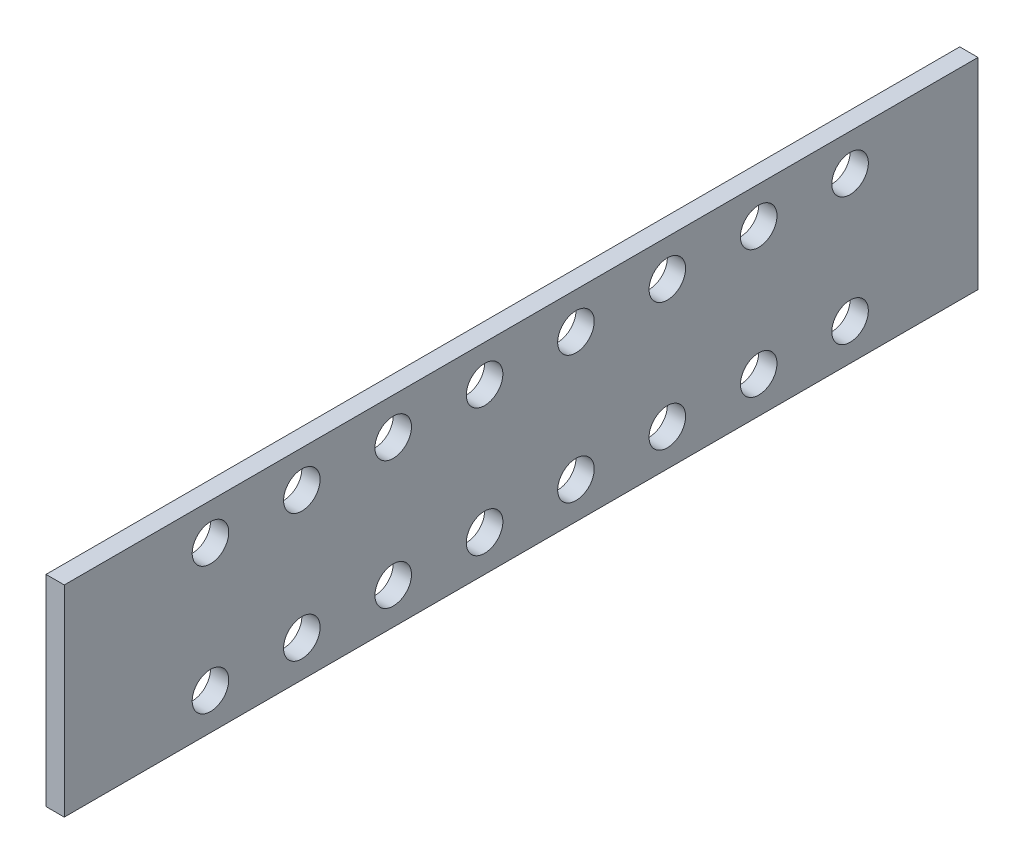
SolidWorks part; units mm, degrees
ref_plane "Front Plane" through (0, 0, 0) normal (0, 0, 1) x (1, 0, 0)
ref_plane "Top Plane" through (0, 0, 0) normal (0, 1, 0) x (1, 0, 0)
ref_plane "Right Plane" through (0, 0, 0) normal (1, 0, 0) x (0, 0, -1)
sketch "Sketch2" plane through (0, 0, 0) normal (1, 0, 0) x (0, 0, -1)
  line L1 (0, 0) -> (500, 0)
  line L2 (0, 0) -> (0, 150)
  line L3 (0, 150) -> (500, 150)
  line L4 (500, 0) -> (500, 150)
extrude "Boss-Extrude1" add sketch "Sketch2" along normal blind 10
sketch "Sketch3" plane through (10, 0, 0) normal (1, 0, 0) x (0, 0, -1)
  line L0 (500, 150) -> (0, 150) construction
  line L1 (0, 150) -> (0, 0) construction
  circle A0 centre (80, 110) radius 10
  dimension "D1" = 20
  dimension "D2" = 40
  dimension "D3" = 80
extrude "Cut-Extrude1" cut sketch "Sketch3" against normal blind 10
ref_plane "Plane1" through (0, 75, 0) normal (0, 1, 0) x (1, 0, 0)
pattern_linear "LPattern1" count 8 spacing 50 along (0, 0, -1) of "Cut-Extrude1"
mirror "Mirror1" about plane through (0, 75, 0) normal (0, 1, 0) of "Cut-Extrude1", "LPattern1"
sketch "Sketch4" plane through (0, 0, 0) normal (-1, 0, 0) x (0, 0, 1)
  line L0 (0, 150) -> (0, 0) construction
  line L1 (-500, 150) -> (0, 150)
  line L2 (-500, 150) -> (-500, 130.0103)
  line L3 (-500, 130.0103) -> (0, 130.0103)
  line L4 (0, 150) -> (0, 130.0103)
  line L6 (-500, 0) -> (0, 0)
  line L7 (-500, 0) -> (-500, 19.9642)
  line L8 (-500, 19.9642) -> (0, 19.9642)
  line L9 (0, 0) -> (0, 19.9642)
extrude "Cut-Extrude2" cut sketch "Sketch4" against normal blind 10
